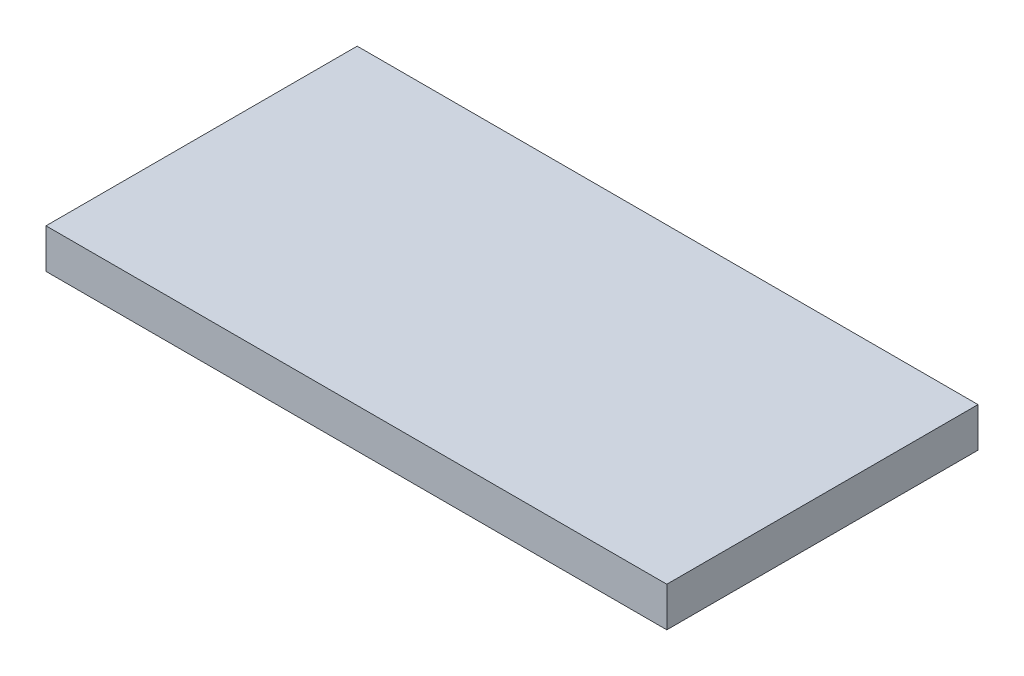
SolidWorks part; units mm, degrees
ref_plane "Alzado" through (0, 0, 0) normal (0, 0, 1) x (1, 0, 0)
ref_plane "Planta" through (0, 0, 0) normal (0, 1, 0) x (1, 0, 0)
ref_plane "Vista lateral" through (0, 0, 0) normal (1, 0, 0) x (0, 0, -1)
sketch "Croquis1" plane through (0, 0, 0) normal (0, 1, 0) x (1, 0, 0)
  line L1 (-399, 200) -> (399, 200)
  line L2 (-399, 200) -> (-399, -200)
  line L3 (-399, -200) -> (399, -200)
  line L4 (399, 200) -> (399, -200)
  line L5 (-399, 200) -> (399, -200) construction
  line L6 (-399, -200) -> (399, 200) construction
  point P0 (0, 0)
  dimension "D1" = 798
  dimension "D2" = 400
extrude "Saliente-Extruir1" add sketch "Croquis1" along normal blind 50.8
shell "Vaciado1" thickness 1.9
